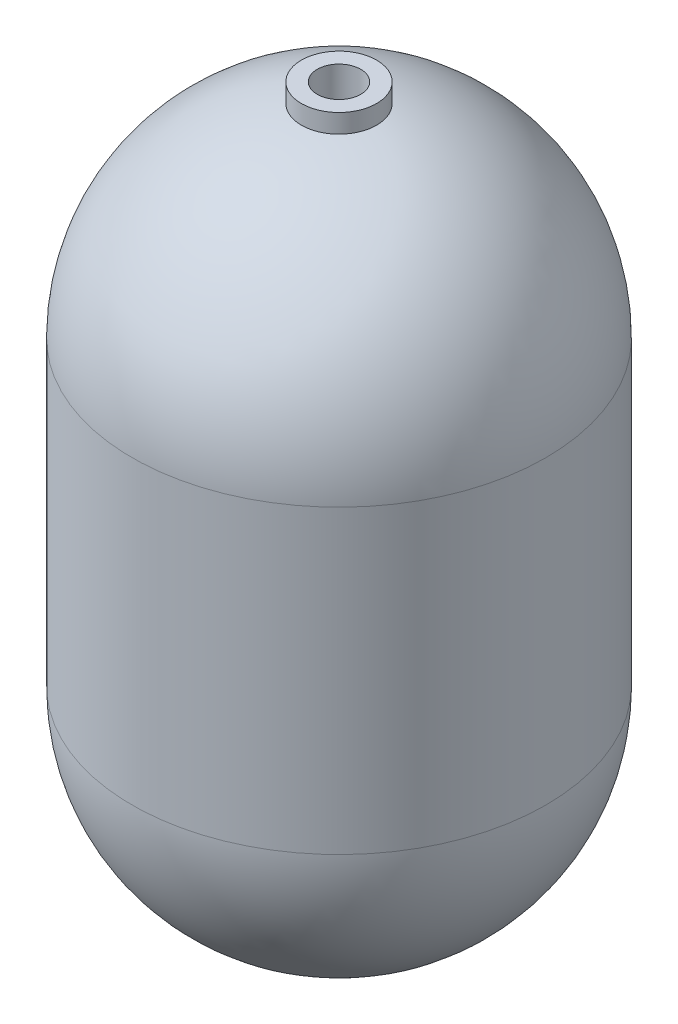
SolidWorks part; units mm, degrees
ref_plane "Front Plane" through (0, 0, 0) normal (0, 0, 1) x (1, 0, 0)
ref_plane "Top Plane" through (0, 0, 0) normal (0, 1, 0) x (1, 0, 0)
ref_plane "Right Plane" through (0, 0, 0) normal (1, 0, 0) x (0, 0, -1)
sketch "Sketch4" plane through (0, 0, 0) normal (0, 0, 1) x (1, 0, 0)
  line L0 (0, 80.4479) -> (0, -171.45) construction
  line L1 (12.7, 75.0358) -> (12.7, 68.6858)
  line L3 (69.85, 0) -> (69.85, -101.6)
  line L4 (63.5, 0) -> (63.5, -101.6)
  line L5 (0, -165.1) -> (0, -171.45)
  line L6 (6.35, 75.0358) -> (12.7, 75.0358)
  line L7 (6.35, 75.0358) -> (2.54, 75.0358)
  line L8 (2.54, 75.0358) -> (2.54, 63.4492)
  line L9 (6.35, 75.0358) -> (6.35, 63.1817) construction
  arc A0 (69.85, -101.6) -> (0, -171.45) centre (0, -101.6) cw
  arc A1 (69.85, 0) -> (12.7, 68.6858) centre (0, 0) ccw
  arc A2 (63.5, 0) -> (6.35, 63.1817) centre (0, 0) ccw
  arc A3 (63.5, -101.6) -> (0, -165.1) centre (0, -101.6) cw
  arc A4 (6.35, 63.1817) -> (2.54, 63.4492) centre (0, 0) ccw
  dimension "D3" = 69.85
  dimension "D1" = 12.7
  dimension "D2" = 101.6
  dimension "D4" = 6.35
  dimension "D6" = 10.16
  dimension "D5" = 6.35
revolve "Revolve1" add sketch "Sketch4" angle 360 about L0
hole_wizard "5/8-18 Tapped Hole2" positions "Sketch8" profile "Sketch7" tap size "5/8-18" standard "ANSI Inch"
sketch "Sketch8" plane through (0, 75.0358, 0) normal (0, 1, 0) x (1, 0, 0)
  point P0 (0, 0)
sketch "Sketch7" plane through (0, 75.0358, 0) normal (1, 0, 0) x (0, 0, 1)
  line L0 (0, 0) -> (0, 43.2734)
  line L1 (0, 43.2734) -> (7.3419, 38.862)
  line L2 (7.3419, 38.862) -> (7.3419, 0)
  line L5 (7.3419, 0) -> (0, 0)
  line L10 (0, 43.2734) -> (-7.3419, 38.862) construction
  line L11 (0, -6.35) -> (0, 107.95) construction
  dimension "Tap Drill Dia." = 14.6837
  dimension "Tap Drill Depth" = 38.862
  dimension "Drill Angle" = 118
cosmetic thread "Hole Thread1" parameters "D1"=11.6974, "D2"=15.875
